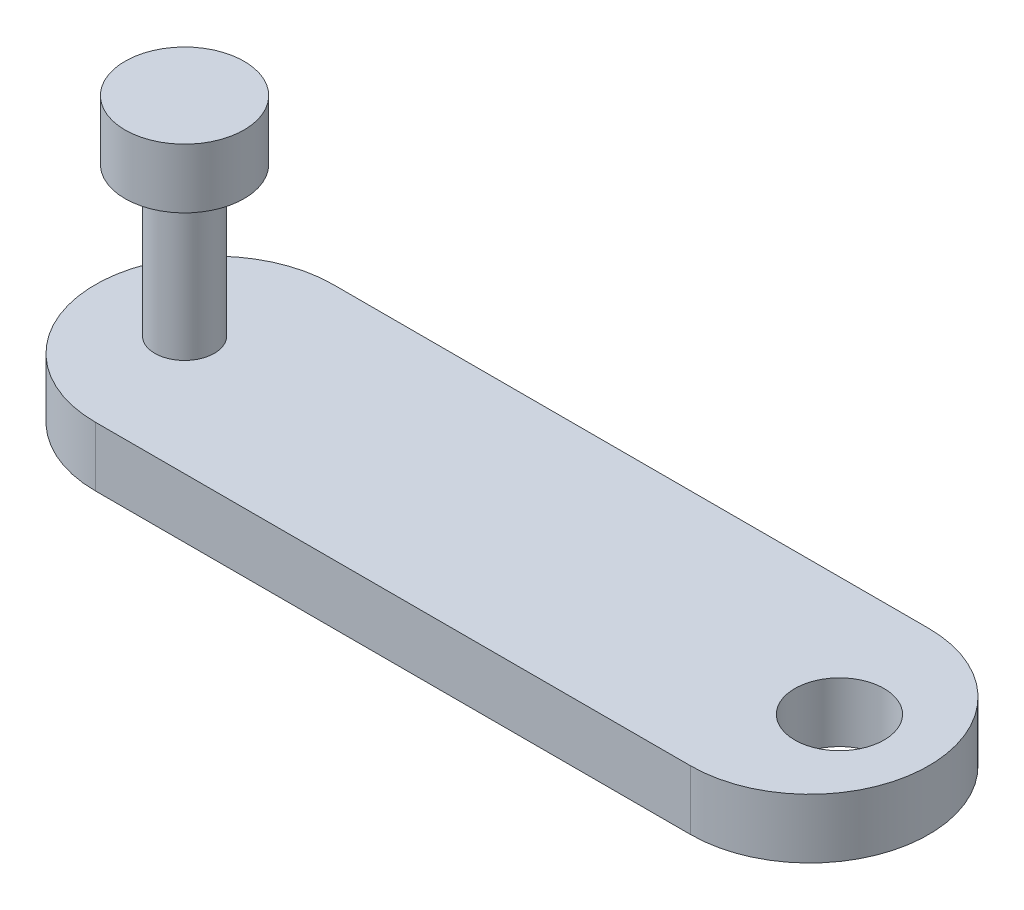
SolidWorks part; units mm, degrees
ref_plane "Front Plane" through (0, 0, 0) normal (0, 0, 1) x (1, 0, 0)
ref_plane "Top Plane" through (0, 0, 0) normal (0, 1, 0) x (1, 0, 0)
ref_plane "Right Plane" through (0, 0, 0) normal (1, 0, 0) x (0, 0, -1)
sketch "Sketch1" plane through (0, 0, 0) normal (0, 1, 0) x (1, 0, 0)
  line L0 (-12.7, 0) -> (12.7, 0) construction
  line L1 (-12.7, 5.08) -> (12.7, 5.08)
  line L2 (-12.7, -5.08) -> (12.7, -5.08)
  arc A0 (-12.7, 5.08) -> (-12.7, -5.08) centre (-12.7, 0) ccw
  arc A1 (12.7, -5.08) -> (12.7, 5.08) centre (12.7, 0) ccw
  point P2 (0, 0)
  dimension "D1" = 25.4
extrude "baton" add sketch "Sketch1" along normal blind 2.54
sketch "Sketch2" plane through (0, 2.54, 0) normal (0, 1, 0) x (1, 0, 0)
  circle A0 centre (-13.97, 0) radius 1.27
  dimension "D1" = 2.54
  dimension "D2" = 13.97
extrude "join" add sketch "Sketch2" along normal blind 6.35
ref_plane "joiner plane" through (0, 8.89, 0) normal (0, 1, 0) x (1, 0, 0)
sketch "Sketch4" plane through (0, 8.89, 0) normal (0, 1, 0) x (1, 0, 0)
  circle A0 centre (-13.97, 0) radius 2.54
  dimension "D1" = 5.08
extrude "joiner cap" add sketch "Sketch4" along normal blind 2.54
sketch "Sketch5" plane through (0, 2.54, 0) normal (0, 1, 0) x (1, 0, 0)
  circle A0 centre (13.97, 0) radius 1.905
  dimension "D1" = 3.81
  dimension "D2" = 13.97
extrude "joiner hole" cut sketch "Sketch5" against normal blind 2.54
